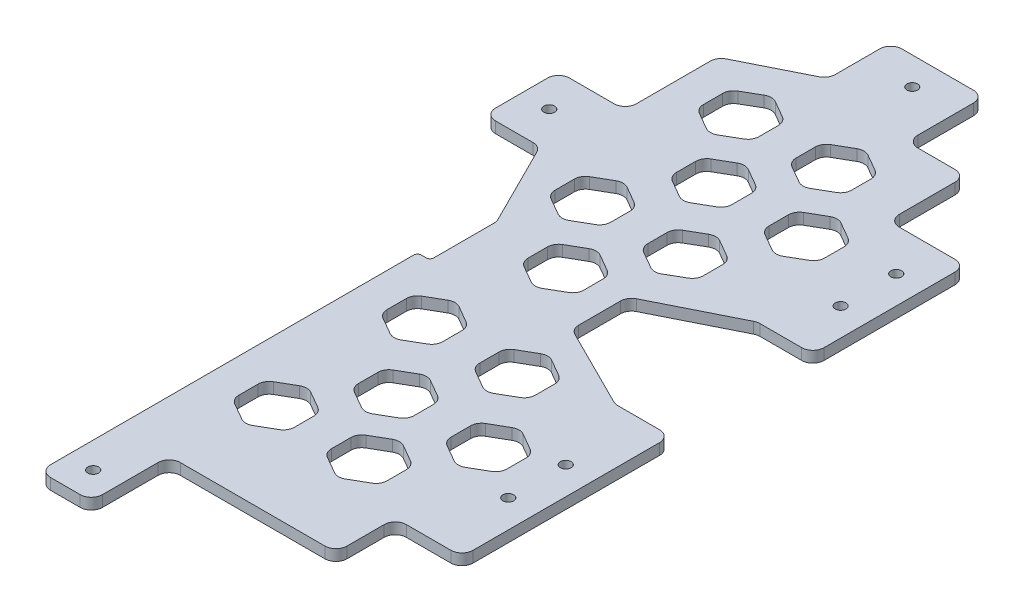
SolidWorks part; units mm, degrees
material "Thornel Mat VMA"
ref_plane "前视基准面" through (0, 0, 0) normal (0, 0, 1) x (1, 0, 0)
ref_plane "上视基准面" through (0, 0, 0) normal (0, 1, 0) x (1, 0, 0)
ref_plane "右视基准面" through (0, 0, 0) normal (1, 0, 0) x (0, 0, -1)
other "Configuration Table"
sketch "草图1" plane through (0, 0, 0) normal (0, 1, 0) x (1, 0, 0)
  line L0 (-35.15, -92.5) -> (-35.15, 92.5) construction
  line L1 (-50.15, -107.5) -> (50.15, -107.5) construction
  line L2 (-50.15, -107.5) -> (-50.15, 107.5) construction
  line L3 (-50.15, 107.5) -> (50.15, 107.5) construction
  line L4 (50.15, -107.5) -> (50.15, 107.5) construction
  line L5 (-50.15, -107.5) -> (50.15, 107.5) construction
  line L6 (-50.15, 107.5) -> (50.15, -107.5) construction
  line L7 (-35.15, 92.5) -> (35.15, 92.5) construction
  line L8 (35.15, -92.5) -> (35.15, 92.5) construction
  line L9 (-35.15, -92.5) -> (35.15, -92.5) construction
  line L10 (-29.85, -107.5) -> (-29.85, -2.5) construction
  line L11 (-9.85, -92.5) -> (-9.85, -107.5) construction
  line L12 (-29.85, -2.5) -> (-25.15, -2.5) construction
  line L13 (-25.15, -2.5) -> (-25.15, 12.5) construction
  line L14 (-35.15, 32.5) -> (-50.15, 32.5) construction
  line L15 (-25.15, 12.5) -> (-35.15, 32.5) construction
  line L16 (15.15, 12.5) -> (15.15, -2.5) construction
  line L17 (15.15, -2.5) -> (35.15, -12.5) construction
  line L18 (35.15, -12.5) -> (50.15, -12.5) construction
  line L19 (15.15, 12.5) -> (35.15, 22.5) construction
  line L20 (35.15, 22.5) -> (50.15, 22.5) construction
  line L21 (-54.2695, 5) -> (53.0339, 5) construction
  line L22 (16.15, 107.5) -> (16.15, 92.5) construction
  line L23 (35.15, 68.5) -> (50.15, 68.5) construction
  line L24 (50.15, 65.5) -> (29.15, 65.5)
  line L25 (-50.15, 82.5) -> (-35.15, 82.5) construction
  line L26 (-35.15, 82.5) -> (-15.15, 92.5) construction
  line L27 (35.15, -73.5) -> (50.15, -73.5) construction
  line L28 (-12.85, -86.5) -> (-12.85, -107.5)
  line L29 (-12.85, -107.5) -> (-26.85, -107.5)
  line L30 (-26.85, -107.5) -> (-26.85, -5.5)
  line L31 (-26.85, -5.5) -> (-23.4729, -5.5)
  line L32 (-23.4729, -5.5) -> (-23.4729, 12.5)
  line L33 (-23.4729, 12.5) -> (-35.15, 35.8541)
  line L34 (-35.15, 35.8541) -> (-50.15, 35.8541)
  line L35 (-50.15, 35.8541) -> (-50.15, 55.8541)
  line L36 (-50.15, 55.8541) -> (-32.15, 55.8541)
  line L39 (-12.15, 90.6459) -> (-12.15, 107.5)
  line L40 (-12.15, 107.5) -> (13.15, 107.5)
  line L41 (13.15, 107.5) -> (13.15, 86.5)
  line L44 (50.15, 65.5) -> (50.15, 24.1771)
  line L45 (50.15, 24.1771) -> (35.15, 24.1771)
  line L46 (-25.15, 12.5) -> (15.15, 12.5) construction
  line L47 (-25.15, -2.5) -> (15.15, -2.5) construction
  line L48 (35.15, 24.1771) -> (11.7959, 12.5)
  line L49 (11.7959, 12.5) -> (11.7959, -2.5)
  line L50 (11.7959, -2.5) -> (35.15, -14.1771)
  line L51 (35.15, -14.1771) -> (50.15, -14.1771)
  line L52 (50.15, -14.1771) -> (50.15, -70.5)
  line L53 (50.15, -70.5) -> (32.15, -70.5)
  line L54 (32.15, -70.5) -> (32.15, -86.5)
  line L55 (32.15, -86.5) -> (-12.85, -86.5)
  line L56 (-15.15, 92.5) -> (-15.15, 107.5) construction
  line L57 (-32.15, 55.8541) -> (-32.15, 80.6459)
  line L58 (-32.15, 80.6459) -> (-12.15, 90.6459)
  line L59 (29.15, 65.5) -> (29.15, 86.5)
  line L60 (29.15, 86.5) -> (13.15, 86.5)
  point P0 (0, 0)
  dimension "D1" = 215
  dimension "D2" = 100.3
  dimension "D4" = 105
  dimension "D5" = 5.3
  dimension "D6" = 20
  dimension "D7" = 4.7
  dimension "D8" = 35
  dimension "D9" = 15
  dimension "D10" = 35
  dimension "D11" = 15
  dimension "D12" = 20
  dimension "D13" = 7.5
  dimension "D14" = 19
  dimension "D15" = 25
  dimension "D16" = 20
  dimension "D17" = 19
  dimension "D18" = 3
  dimension "D19" = 3
  dimension "D20" = 6
  dimension "D21" = 3
  dimension "D22" = 3
  dimension "D23" = 3
  dimension "D24" = 3
  dimension "D25" = 3
  dimension "D26" = 24
  dimension "D27" = 3
  dimension "D28" = 3
  dimension "D29" = 3
  dimension "D30" = 20
  dimension "D31" = 3
  dimension "D32" = 6
  dimension "D33" = 3
  dimension "D34" = 6
  dimension "D3" = 15
extrude "凸台-拉伸1" add sketch "草图1" along normal blind 3
fillet "圆角1" radius 3 25 edges at (32.15, 1.5, 70.5) (-12.85, 1.5, 86.5) (-12.85, 1.5, 107.5) (-26.85, 1.5, 107.5) (-23.4729, 1.5, -12.5) (-35.15, 1.5, -35.8541) (-50.15, 1.5, -35.8541) (-50.15, 1.5, -55.8541) (-12.15, 1.5, -107.5) (13.15, 1.5, -107.5) (50.15, 1.5, -24.1771) (35.15, 1.5, -24.1771) (11.7959, 1.5, -12.5) (11.7959, 1.5, 2.5) (35.15, 1.5, 14.1771) (50.15, 1.5, 14.1771) (32.15, 1.5, 86.5) (50.15, 1.5, 70.5) (29.15, 1.5, -86.5) (50.15, 1.5, -65.5) (-32.15, 1.5, -55.8541) (-32.15, 1.5, -80.6459) (-12.15, 1.5, -90.6459) (13.15, 1.5, -86.5) (29.15, 1.5, -65.5)
fillet "圆角2" radius 1 2 edges at (-26.85, 1.5, 5.5) (-23.4729, 1.5, 5.5)
sketch "草图2" plane through (0, 3, 0) normal (0, 1, 0) x (1, 0, 0)
  line L0 (-27.2327, 100) -> (45.5671, 100) construction
  line L1 (-42.65, 71.8095) -> (-42.65, -83.5842) construction
  line L2 (42.65, 78.6701) -> (42.65, -87.3285) construction
  line L3 (-44.3254, -100) -> (0, -100) construction
  line L4 (-23.85, -107.5) -> (-15.85, -107.5) construction
  line L5 (50.15, -67.5) -> (50.15, -17.1771) construction
  line L6 (-50.15, 52.8541) -> (-50.15, 38.8541) construction
  line L7 (10.15, 107.5) -> (-9.15, 107.5) construction
  line L8 (-26.85, -6.5) -> (-26.85, -104.5) construction
  line L9 (35.15, -70.5) -> (47.15, -70.5) construction
  line L10 (35.8582, 24.1771) -> (47.15, 24.1771) construction
  line L11 (-47.15, 35.8541) -> (-37.0041, 35.8541) construction
  line L12 (13.15, 89.5) -> (13.15, 104.5) construction
  circle A0 centre (-19.85, -100) radius 1.45
  circle A1 centre (42.65, -50.5) radius 1.45
  circle A2 centre (42.65, -35) radius 1.45
  circle A3 centre (-42.65, 45.8541) radius 1.45
  circle A4 centre (1.15, 100) radius 1.45
  circle A5 centre (42.65, 54.1771) radius 1.45
  circle A6 centre (42.65, 39.1771) radius 1.45
  dimension "D5" = 2.9
  dimension "D6" = 7
  dimension "D7" = 20
  dimension "D8" = 15.5
  dimension "D9" = 15
  dimension "D10" = 15
  dimension "D12" = 12
  dimension "D1" = 7.5
  dimension "D2" = 7.5
  dimension "D3" = 7.5
  dimension "D4" = 7.5
  dimension "D11" = 10
extrude "切除-拉伸1" cut sketch "草图2" against normal through all
sketch "草图3" plane through (0, 3, 0) normal (0, 1, 0) x (1, 0, 0)
  line L0 (9.5719, 78.9848) -> (2.0719, 74.6546)
  line L1 (-15.4281, 78.9848) -> (-22.9281, 74.6546)
  line L2 (-22.9281, 74.6546) -> (-22.9281, 65.9944)
  line L3 (-22.9281, 65.9944) -> (-15.4281, 61.6643)
  line L4 (-15.4281, 61.6643) -> (-7.9281, 65.9944)
  line L5 (-7.9281, 65.9944) -> (-7.9281, 74.6546)
  line L6 (-7.9281, 74.6546) -> (-15.4281, 78.9848)
  line L7 (4.2943, 55.1531) -> (-3.2057, 59.4833)
  line L8 (-3.2057, 59.4833) -> (-10.7057, 55.1531)
  line L9 (-10.7057, 55.1531) -> (-10.7057, 46.4929)
  line L10 (-10.7057, 46.4929) -> (-3.2057, 42.1628)
  line L11 (-3.2057, 42.1628) -> (4.2943, 46.4929)
  line L12 (4.2943, 46.4929) -> (4.2943, 55.1531)
  line L13 (2.0719, 74.6546) -> (2.0719, 65.9944)
  line L14 (2.0719, 65.9944) -> (9.5719, 61.6643)
  line L15 (9.5719, 61.6643) -> (17.0719, 65.9944)
  line L16 (17.0719, 65.9944) -> (17.0719, 74.6546)
  line L17 (17.0719, 74.6546) -> (9.5719, 78.9848)
  line L18 (29.2943, 55.1531) -> (21.7943, 59.4833)
  line L19 (21.7943, 59.4833) -> (14.2943, 55.1531)
  line L20 (14.2943, 55.1531) -> (14.2943, 46.4929)
  line L21 (14.2943, 46.4929) -> (21.7943, 42.1628)
  line L22 (21.7943, 42.1628) -> (29.2943, 46.4929)
  line L23 (29.2943, 46.4929) -> (29.2943, 55.1531)
  line L24 (9.5719, 38.9848) -> (2.0719, 34.6546)
  line L25 (2.0719, 34.6546) -> (2.0719, 25.9944)
  line L26 (2.0719, 25.9944) -> (9.5719, 21.6643)
  line L27 (9.5719, 21.6643) -> (17.0719, 25.9944)
  line L28 (17.0719, 25.9944) -> (17.0719, 34.6546)
  line L29 (17.0719, 34.6546) -> (9.5719, 38.9848)
  line L36 (-15.4281, 38.9848) -> (-22.9281, 34.6546)
  line L37 (-22.9281, 34.6546) -> (-22.9281, 25.9944)
  line L38 (-22.9281, 25.9944) -> (-15.4281, 21.6643)
  line L39 (-15.4281, 21.6643) -> (-7.9281, 25.9944)
  line L40 (-7.9281, 25.9944) -> (-7.9281, 34.6546)
  line L41 (-7.9281, 34.6546) -> (-15.4281, 38.9848)
  line L42 (4.2943, 15.1531) -> (-3.2057, 19.4833)
  line L43 (-3.2057, 19.4833) -> (-10.7057, 15.1531)
  line L44 (-10.7057, 15.1531) -> (-10.7057, 6.4929)
  line L45 (-10.7057, 6.4929) -> (-3.2057, 2.1628)
  line L46 (-3.2057, 2.1628) -> (4.2943, 6.4929)
  line L47 (4.2943, 6.4929) -> (4.2943, 15.1531)
  line L48 (29.2943, 15.1531) -> (21.7943, 19.4833) [skipped]
  line L49 (21.7943, 19.4833) -> (14.2943, 15.1531) [skipped]
  line L50 (14.2943, 15.1531) -> (14.2943, 6.4929) [skipped]
  line L51 (14.2943, 6.4929) -> (21.7943, 2.1628) [skipped]
  line L52 (21.7943, 2.1628) -> (29.2943, 6.4929) [skipped]
  line L53 (29.2943, 6.4929) -> (29.2943, 15.1531) [skipped]
  line L54 (22.311, -15.9266) -> (14.811, -11.5965)
  line L55 (-2.689, -15.9266) -> (-10.189, -11.5965)
  line L56 (-10.189, -11.5965) -> (-17.689, -15.9266)
  line L57 (-17.689, -15.9266) -> (-17.689, -24.5869)
  line L58 (-17.689, -24.5869) -> (-10.189, -28.917)
  line L59 (-10.189, -28.917) -> (-2.689, -24.5869)
  line L60 (-2.689, -24.5869) -> (-2.689, -15.9266)
  line L61 (3.2255, -32.7192) -> (-4.2745, -37.0493)
  line L62 (-4.2745, -37.0493) -> (-4.2745, -45.7096)
  line L63 (-4.2745, -45.7096) -> (3.2255, -50.0397)
  line L64 (3.2255, -50.0397) -> (10.7255, -45.7096)
  line L65 (10.7255, -45.7096) -> (10.7255, -37.0493)
  line L66 (10.7255, -37.0493) -> (3.2255, -32.7192)
  line L67 (14.811, -11.5965) -> (7.311, -15.9266)
  line L68 (7.311, -15.9266) -> (7.311, -24.5869)
  line L69 (7.311, -24.5869) -> (14.811, -28.917)
  line L70 (14.811, -28.917) -> (22.311, -24.5869)
  line L71 (22.311, -24.5869) -> (22.311, -15.9266)
  line L72 (28.2255, -32.7192) -> (20.7255, -37.0493)
  line L73 (20.7255, -37.0493) -> (20.7255, -45.7096)
  line L74 (20.7255, -45.7096) -> (28.2255, -50.0397)
  line L75 (28.2255, -50.0397) -> (35.7255, -45.7096)
  line L76 (35.7255, -45.7096) -> (35.7255, -37.0493)
  line L77 (35.7255, -37.0493) -> (28.2255, -32.7192)
  line L78 (22.311, -55.9266) -> (14.811, -51.5965)
  line L79 (14.811, -51.5965) -> (7.311, -55.9266)
  line L80 (7.311, -55.9266) -> (7.311, -64.5869)
  line L81 (7.311, -64.5869) -> (14.811, -68.917)
  line L82 (14.811, -68.917) -> (22.311, -64.5869)
  line L83 (22.311, -64.5869) -> (22.311, -55.9266)
  line L90 (-2.689, -55.9266) -> (-10.189, -51.5965)
  line L91 (-10.189, -51.5965) -> (-17.689, -55.9266)
  line L92 (-17.689, -55.9266) -> (-17.689, -64.5869)
  line L93 (-17.689, -64.5869) -> (-10.189, -68.917)
  line L94 (-10.189, -68.917) -> (-2.689, -64.5869)
  line L95 (-2.689, -64.5869) -> (-2.689, -55.9266)
  line L102 (-4.2745, -77.0493) -> (-4.2745, -85.7096) [skipped]
  line L103 (10.7255, -85.7096) -> (10.7255, -77.0493) [skipped]
  line L104 (10.7255, -77.0493) -> (3.2255, -72.7192) [skipped]
  line L105 (3.2255, -72.7192) -> (-4.2745, -77.0493) [skipped]
  line L106 (3.2255, -90.0397) -> (10.7255, -85.7096) [skipped]
  line L107 (-4.2745, -85.7096) -> (3.2255, -90.0397) [skipped]
  line L108 (20.7255, -77.0493) -> (20.7255, -85.7096) [skipped]
  line L109 (35.7255, -85.7096) -> (35.7255, -77.0493) [skipped]
  line L110 (35.7255, -77.0493) -> (28.2255, -72.7192) [skipped]
  line L111 (28.2255, -72.7192) -> (20.7255, -77.0493) [skipped]
  line L112 (20.7255, -85.7096) -> (28.2255, -90.0397) [skipped]
  line L113 (28.2255, -90.0397) -> (35.7255, -85.7096) [skipped]
  circle A0 centre (-15.4281, 70.3245) radius 7.5 construction
  circle A1 centre (-3.2057, 50.823) radius 7.5 construction
  circle A2 centre (-10.189, -20.2568) radius 7.5 construction
  circle A3 centre (3.2255, -41.3794) radius 7.5 construction
  dimension "D1" = 15
  dimension "D2" = 15
  dimension "D6" = 15
  dimension "D7" = 15
  dimension "D3" = 8
  dimension "D8" = 10
  dimension "D4" = 2
  dimension "D5" = 2
  dimension "D9" = 2
  dimension "D10" = 2
extrude "切除-拉伸2" cut sketch "草图3" against normal through all
fillet "圆角3" radius 3 78 edges at (-7.9281, 1.5, -65.9944) (-15.4281, 1.5, -61.6643) (-22.9281, 1.5, -65.9944) (-22.9281, 1.5, -74.6546) (-7.9281, 1.5, -74.6546) (-10.189, 1.5, 68.917) (-17.689, 1.5, 64.5869) (-17.689, 1.5, 55.9266) (-10.189, 1.5, 51.5965) (-2.689, 1.5, 55.9266) (-2.689, 1.5, 64.5869) (14.811, 1.5, 68.917) (7.311, 1.5, 64.5869) (7.311, 1.5, 55.9266) (14.811, 1.5, 51.5965) (22.311, 1.5, 55.9266) (22.311, 1.5, 64.5869) (35.7255, 1.5, 45.7096) (28.2255, 1.5, 50.0397) (20.7255, 1.5, 45.7096) (20.7255, 1.5, 37.0493) (28.2255, 1.5, 32.7192) (35.7255, 1.5, 37.0493) (14.811, 1.5, 28.917) (7.311, 1.5, 24.5869) (7.311, 1.5, 15.9266) (14.811, 1.5, 11.5965) (22.311, 1.5, 15.9266) (22.311, 1.5, 24.5869) (21.7943, 1.5, -42.1628) (14.2943, 1.5, -46.4929) (14.2943, 1.5, -55.1531) (21.7943, 1.5, -59.4833) (29.2943, 1.5, -55.1531) (29.2943, 1.5, -46.4929) (17.0719, 1.5, -65.9944) (9.5719, 1.5, -61.6643) (2.0719, 1.5, -65.9944) (2.0719, 1.5, -74.6546) (17.0719, 1.5, -74.6546) (-10.189, 1.5, 28.917) (-17.689, 1.5, 24.5869) (-17.689, 1.5, 15.9266) (-10.189, 1.5, 11.5965) (-2.689, 1.5, 15.9266) (-2.689, 1.5, 24.5869) (-3.2057, 1.5, -42.1628) (-10.7057, 1.5, -46.4929) (-10.7057, 1.5, -55.1531) (-3.2057, 1.5, -59.4833) (4.2943, 1.5, -55.1531) (4.2943, 1.5, -46.4929) (17.0719, 1.5, -25.9944) (9.5719, 1.5, -21.6643) (2.0719, 1.5, -25.9944) (2.0719, 1.5, -34.6546) (9.5719, 1.5, -38.9848) (17.0719, 1.5, -34.6546) (-7.9281, 1.5, -25.9944) (-15.4281, 1.5, -21.6643) (-22.9281, 1.5, -25.9944) (-22.9281, 1.5, -34.6546) (-15.4281, 1.5, -38.9848) (-7.9281, 1.5, -34.6546) (-3.2057, 1.5, -2.1628) (-10.7057, 1.5, -6.4929) (-10.7057, 1.5, -15.1531) (-3.2057, 1.5, -19.4833) (4.2943, 1.5, -15.1531) (4.2943, 1.5, -6.4929) (10.7255, 1.5, 45.7096) (3.2255, 1.5, 50.0397) (-4.2745, 1.5, 45.7096) (-4.2745, 1.5, 37.0493) (3.2255, 1.5, 32.7192) (10.7255, 1.5, 37.0493) (9.5719, 1.5, -78.9848) (-15.4281, 1.5, -78.9848)
